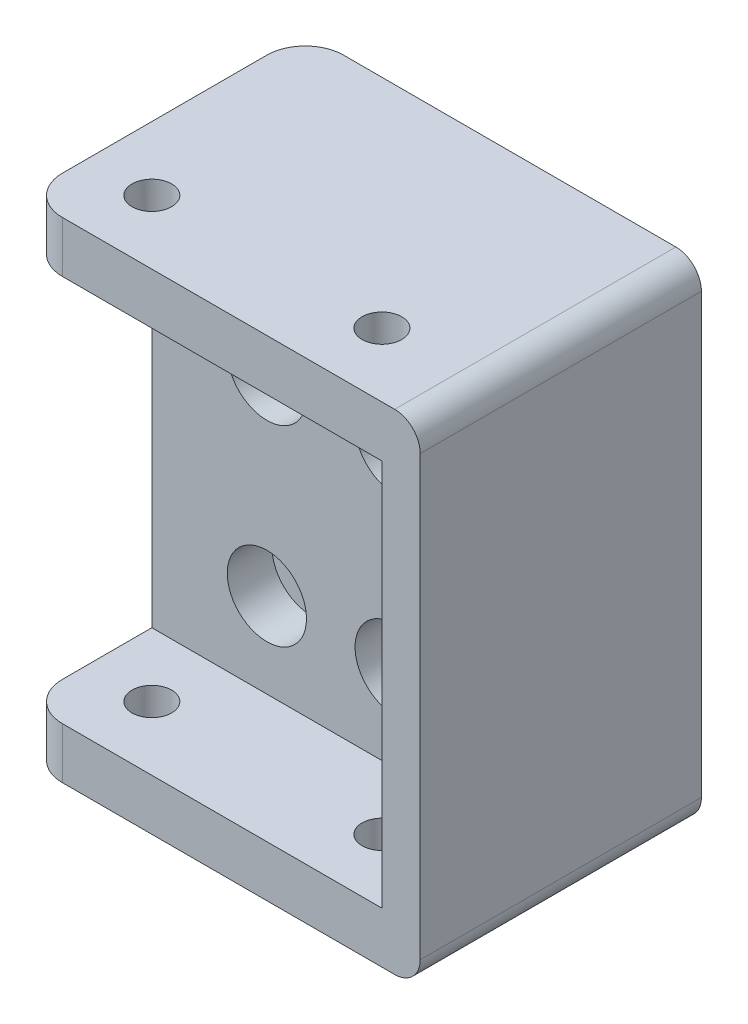
SolidWorks part; units mm, degrees
ref_plane "前视基准面" through (0, 0, 0) normal (0, 0, 1) x (1, 0, 0)
ref_plane "上视基准面" through (0, 0, 0) normal (0, 1, 0) x (1, 0, 0)
ref_plane "右视基准面" through (0, 0, 0) normal (1, 0, 0) x (0, 0, -1)
other "Configuration Table"
sketch "草图1" plane through (0, 0, 0) normal (0, 0, 1) x (1, 0, 0)
  line L1 (-5, 7.5) -> (5, 7.5) construction
  line L2 (-5, 7.5) -> (-5, -7.5) construction
  line L3 (-5, -7.5) -> (5, -7.5) construction
  line L4 (5, 7.5) -> (5, -7.5) construction
  line L5 (-5, 7.5) -> (5, -7.5) construction
  line L6 (-5, -7.5) -> (5, 7.5) construction
  line L7 (-14, 10.15) -> (14, 10.15)
  line L8 (-14, 10.15) -> (-14, -10.15)
  line L9 (-14, -10.15) -> (14, -10.15)
  line L10 (14, 10.15) -> (14, -10.15)
  line L11 (-14, 10.15) -> (14, -10.15) construction
  line L12 (-14, -10.15) -> (14, 10.15) construction
  circle A0 centre (-5, 7.5) radius 1.5
  circle A1 centre (5, 7.5) radius 1.5
  circle A2 centre (5, -7.5) radius 1.5
  circle A3 centre (-5, -7.5) radius 1.5
  point P0 (0, 0)
  point P6 (0, 0)
  dimension "D4" = 3
  dimension "D1" = 15
  dimension "D2" = 10
  dimension "D3" = 28
  dimension "D5" = 20.3
extrude "凸台-拉伸1" add sketch "草图1" along normal blind 5
sketch "草图2" plane through (0, 0, 5) normal (0, 0, 1) x (1, 0, 0)
  line L0 (-14, 0) -> (14, 0)
  line L1 (14, 10.15) -> (-14, 10.15)
  line L2 (-14, -10.15) -> (14, -10.15)
  line L3 (-14, -10.15) -> (-14, -14.15)
  line L4 (14, -10.15) -> (14, 10.15)
  line L5 (14, 10.15) -> (-14, 10.15)
  line L6 (-14, 10.15) -> (-14, -10.15)
  line L7 (-14, -10.15) -> (14, -10.15)
  line L8 (14, -10.15) -> (14, 10.15)
  line L9 (14, 10.15) -> (-14, 10.15)
  line L10 (-14, 10.15) -> (-14, -10.15)
  line L11 (-14, -10.15) -> (14, -10.15)
  line L12 (-14, -14.15) -> (14, -14.15)
  line L13 (14, -10.15) -> (14, -14.15)
  line L14 (14, 10.15) -> (14, 16.15)
  line L15 (-14, 10.15) -> (-14, 16.15)
  line L16 (14, 16.15) -> (-14, 16.15)
  line M11 (14, 10.15) -> (-14, 10.15)
  line M13 (-14, -10.15) -> (14, -10.15)
  dimension "D2" = 4
  dimension "D3" = 6
  dimension "D1" = 0
extrude "凸台-拉伸2" add sketch "草图2" against normal blind 10 contours L14 L16 L15 L1 M11 | L13 L3 L12 M13
sketch "草图3" plane through (0, 0, -5) normal (0, 0, -1) x (-1, 0, 0)
  line L4 (-14, 16.15) -> (-14, 10.15)
  line L5 (-14, 10.15) -> (14, 10.15)
  line L6 (14, 10.15) -> (14, 16.15)
  line L7 (14, 16.15) -> (-14, 16.15)
  line L8 (-14, 16.15) -> (-14, 10.15)
  line L9 (-14, 10.15) -> (14, 10.15)
  line L10 (14, 10.15) -> (14, 16.15)
  line L11 (14, 16.15) -> (-14, 16.15)
  dimension "D1" = 0
extrude "凸台-拉伸3" add sketch "草图3" along normal blind 5
sketch "草图4" plane through (0, 0, 5) normal (0, 0, 1) x (1, 0, 0)
  line L0 (14, 16.15) -> (-14, 16.15) construction
  line L2 (0, 13.15) -> (0, 0) construction
  circle A0 centre (-9, 13.15) radius 1.5
  circle A1 centre (0, 13.15) radius 1.5 construction
  circle A2 centre (9, 13.15) radius 1.5
  dimension "D1" = 3
  dimension "D2" = 3
  dimension "D5" = 9
  dimension "D4" = 3
extrude "切除-拉伸1" cut sketch "草图4" against normal through all
sketch "草图5" plane through (-14, 0, 0) normal (-1, 0, 0) x (0, 0, 1)
  line L0 (0, 16.15) -> (0, -14.15)
  line L8 (0, 10.15) -> (0, -10.15)
  line L9 (0, -10.15) -> (-5, -10.15)
  line L10 (-5, -10.15) -> (-5, -14.15)
  line L11 (-5, -14.15) -> (5, -14.15)
  line L12 (5, -14.15) -> (5, 16.15)
  line L13 (5, 16.15) -> (-10, 16.15)
  line L14 (-10, 16.15) -> (-10, 10.15)
  line L15 (-10, 10.15) -> (0, 10.15)
  line L16 (0, 10.15) -> (0, -10.15)
  line L17 (0, -10.15) -> (-5, -10.15)
  line L18 (-5, -10.15) -> (-5, -14.15)
  line L19 (-5, -14.15) -> (5, -14.15)
  line L20 (5, -14.15) -> (5, 16.15)
  line L21 (5, 16.15) -> (-10, 16.15)
  line L22 (-10, 16.15) -> (-10, 10.15)
  line L23 (-10, 10.15) -> (0, 10.15)
  line M10 (0, -10.15) -> (-5, -10.15)
  line M11 (-5, -10.15) -> (-5, -14.15)
  line M12 (-5, -14.15) -> (5, -14.15)
  line M14 (5, 16.15) -> (-10, 16.15)
  line M15 (-10, 16.15) -> (-10, 10.15)
  line M16 (-10, 10.15) -> (0, 10.15)
  dimension "D1" = 0
extrude "切除-拉伸2" cut sketch "草图5" against normal through all contours L0 M14 M15 M16 | L0 M10 M11 M12
sketch "草图6" plane through (0, 0, 5) normal (0, 0, 1) x (1, 0, 0)
  line L4 (14, -14.15) -> (14, 16.15)
  line L5 (14, 16.15) -> (-14, 16.15)
  line L6 (-14, 16.15) -> (-14, -14.15)
  line L7 (-14, -14.15) -> (14, -14.15)
  line L8 (14, -14.15) -> (14, 16.15)
  line L9 (14, 16.15) -> (-14, 16.15)
  line L10 (-14, 16.15) -> (-14, -14.15)
  line L11 (-14, -14.15) -> (14, -14.15)
  dimension "D1" = 0
extrude "切除-拉伸3" cut sketch "草图6" against normal blind 1
sketch "草图7" plane through (0, 0, 4) normal (0, 0, 1) x (1, 0, 0)
  line L0 (-14, -14.15) -> (14, -14.15)
  line L1 (-14, -14.15) -> (-14, -18.15)
  line L2 (14, -14.15) -> (14, -18.15)
  line L3 (-14, -18.15) -> (14, -18.15)
  line L4 (-14, -14.15) -> (14, -14.15)
  line L5 (14, -14.15) -> (14, 16.15)
  line L6 (14, 16.15) -> (-14, 16.15)
  line L7 (-14, 16.15) -> (-14, -14.15)
  line L8 (-14, -14.15) -> (14, -14.15)
  line L9 (14, -14.15) -> (14, 16.15)
  line L10 (14, 16.15) -> (-14, 16.15)
  line L11 (-14, 16.15) -> (-14, -14.15)
  line L12 (-14, 16.15) -> (14, 16.15)
  line L13 (-14, 16.15) -> (-14, 20.15)
  line L14 (14, 16.15) -> (14, 20.15)
  line L15 (-14, 20.15) -> (14, 20.15)
  line M11 (-14, -14.15) -> (14, -14.15)
  line M13 (14, 16.15) -> (-14, 16.15)
  dimension "D2" = 4
  dimension "D3" = 4
  dimension "D1" = 0
extrude "凸台-拉伸4" add sketch "草图7" against normal blind 10 and the other way blind 12 contours L15 L13 L14 M13 | L1 L3 L2 M11
sketch "草图9" plane through (0, 0, 4) normal (0, 0, 1) x (1, 0, 0)
  line L1 (-7.369, 10.325) -> (-5.738, 13.15)
  line L2 (-5.738, 13.15) -> (-7.369, 15.975)
  line L3 (-7.369, 15.975) -> (-10.631, 15.975)
  line L4 (-10.631, 15.975) -> (-12.262, 13.15)
  line L5 (-12.262, 13.15) -> (-10.631, 10.325)
  line L6 (-10.631, 10.325) -> (-7.369, 10.325)
  line L7 (10.631, 10.325) -> (12.262, 13.15)
  line L8 (12.262, 13.15) -> (10.631, 15.975)
  line L9 (10.631, 15.975) -> (7.369, 15.975)
  line L10 (7.369, 15.975) -> (5.738, 13.15)
  line L11 (5.738, 13.15) -> (7.369, 10.325)
  line L12 (7.369, 10.325) -> (10.631, 10.325)
  circle A0 centre (5, -7.5) radius 1.5 construction
  circle A1 centre (-5, -7.5) radius 1.5 construction
  circle A2 centre (9, 13.15) radius 1.5 construction
  circle A3 centre (5, 7.5) radius 1.5 construction
  circle A4 centre (-5, 7.5) radius 1.5 construction
  circle A5 centre (-9, 13.15) radius 1.5 construction
  circle A6 centre (5, -7.5) radius 1.5
  circle A7 centre (-5, -7.5) radius 1.5
  circle A8 centre (9, 13.15) radius 1.5
  circle A9 centre (5, 7.5) radius 1.5
  circle A10 centre (-5, 7.5) radius 1.5
  circle A11 centre (-9, 13.15) radius 1.5
  circle A13 centre (-5, 7.5) radius 3.1
  circle A14 centre (5, 7.5) radius 3.1
  circle A16 centre (5, -7.5) radius 3.1
  circle A17 centre (-5, -7.5) radius 3.1
  circle A18 centre (-9, 13.15) radius 2.825 construction
  circle A19 centre (9, 13.15) radius 2.825 construction
  dimension "D1" = 5.65
  dimension "D2" = 1.6
extrude "切除-拉伸4" cut sketch "草图9" against normal blind 1.5 and the other way through all
sketch "草图10" plane through (0, -14.15, 0) normal (0, 1, 0) x (1, 0, 0)
  line L0 (0, -4) -> (0, -16)
  line L4 (14, -4) -> (-14, -4)
  line L5 (-14, -4) -> (-14, -16)
  line L6 (-14, -16) -> (14, -16)
  line L7 (14, -16) -> (14, -4)
  line L8 (14, -4) -> (-14, -4)
  line L9 (-14, -4) -> (-14, -16)
  line L10 (-14, -16) -> (14, -16)
  line L11 (14, -16) -> (14, -4)
  circle A0 centre (-9, -11) radius 1.55
  circle A1 centre (9, -11) radius 1.55
  dimension "D2" = 3.1
  dimension "D3" = 5
  dimension "D4" = 5
  dimension "D1" = 0
extrude "切除-拉伸5" cut sketch "草图10" against normal through all and the other way through all contours A0 | A1
sketch "草图11" plane through (14, 0, 0) normal (1, 0, 0) x (0, 0, -1)
  line L0 (-16, 16.15) -> (-16, -14.15)
  line L1 (6, 18.4397) -> (6, -14.15)
  line L12 (-4, 16.15) -> (-4, -14.15)
  line L13 (-4, -14.15) -> (-16, -14.15)
  line L14 (-16, -14.15) -> (-16, -18.15)
  line L15 (-16, -18.15) -> (6, -18.15)
  line L16 (6, -18.15) -> (6, -14.15)
  line L17 (6, -14.15) -> (0, -14.15)
  line L18 (0, -14.15) -> (0, 16.15)
  line L19 (0, 16.15) -> (6, 16.15)
  line L20 (6, 16.15) -> (6, 20.15)
  line L21 (6, 20.15) -> (-16, 20.15)
  line L22 (-16, 20.15) -> (-16, 16.15)
  line L23 (-16, 16.15) -> (-4, 16.15)
  line L24 (-4, 16.15) -> (-4, -14.15)
  line L25 (-4, -14.15) -> (-16, -14.15)
  line L26 (-16, -14.15) -> (-16, -18.15)
  line L27 (-16, -18.15) -> (6, -18.15)
  line L28 (6, -18.15) -> (6, -14.15)
  line L29 (6, -14.15) -> (0, -14.15)
  line L30 (0, -14.15) -> (0, 16.15)
  line L31 (0, 16.15) -> (6, 16.15)
  line L32 (6, 16.15) -> (6, 20.15)
  line L33 (6, 20.15) -> (-16, 20.15)
  line L34 (-16, 20.15) -> (-16, 16.15)
  line L38 (-16, 16.15) -> (-4, 16.15)
  line M13 (-4, 16.15) -> (-4, -14.15)
  line M14 (-4, -14.15) -> (-16, -14.15)
  line M15 (-16, -14.15) -> (-16, -18.15)
  line M16 (-16, -18.15) -> (6, -18.15)
  line M17 (6, -18.15) -> (6, -14.15)
  line M18 (6, -14.15) -> (0, -14.15)
  line M19 (0, -14.15) -> (0, 16.15)
  line M20 (0, 16.15) -> (6, 16.15)
  line M21 (6, 16.15) -> (6, 20.15)
  line M22 (6, 20.15) -> (-16, 20.15)
  line M23 (-16, 20.15) -> (-16, 16.15)
  line M24 (-16, 16.15) -> (-4, 16.15)
  dimension "D1" = 0
extrude "凸台-拉伸5" add sketch "草图11" along normal blind 3 contours M24 M13 M14 M15 M16 M17 M18 M19 M20 M21 M22 M23 | L0 M24 M14 M13 | L1 M20 M19 M18
fillet "圆角1" radius 2 2 edges at (17, -18.15, 5) (17, 20.15, 5)
fillet "圆角2" radius 3 4 edges at (-14, 18.15, 16) (-14, 18.15, -6) (-14, -16.15, -6) (-14, -16.15, 16)
sketch "草图13" plane through (0, 0, 4) normal (0, 0, 1) x (1, 0, 0)
  line L0 (-10.631, 15.975) -> (-7.369, 15.975) construction
  line L1 (-12.262, 13.15) -> (-10.631, 15.975) construction
  line L2 (-10.631, 15.975) -> (-7.369, 15.975)
  line L3 (-12.262, 13.15) -> (-10.631, 15.975)
  line L4 (-7.369, 15.975) -> (-5.738, 13.15) construction
  line L5 (-5.738, 13.15) -> (-7.369, 10.325) construction
  line L6 (14, 16.15) -> (-14, 16.15)
  line L7 (-7.369, 10.325) -> (-10.631, 10.325) construction
  line L8 (-10.631, 10.325) -> (-12.262, 13.15) construction
  line L9 (-14, 16.15) -> (-14, -14.15)
  line L10 (-14, -14.15) -> (14, -14.15)
  line L11 (14, -14.15) -> (14, 16.15)
  line L12 (14, 16.15) -> (-14, 16.15)
  line L15 (-14, 16.15) -> (-14, -14.15)
  line L16 (-14, -14.15) -> (14, -14.15)
  line L17 (14, -14.15) -> (14, 16.15)
  line L18 (-7.369, 15.975) -> (-5.738, 13.15)
  line L19 (-5.738, 13.15) -> (-7.369, 10.325)
  line L20 (-7.369, 10.325) -> (-10.631, 10.325)
  line L21 (-10.631, 10.325) -> (-12.262, 13.15)
  line L22 (10.631, 10.325) -> (7.369, 10.325) construction
  line L23 (7.369, 10.325) -> (5.738, 13.15) construction
  line L24 (12.262, 13.15) -> (10.631, 10.325) construction
  line L25 (10.631, 15.975) -> (12.262, 13.15) construction
  line L26 (7.369, 15.975) -> (10.631, 15.975) construction
  line L27 (5.738, 13.15) -> (7.369, 15.975) construction
  line L28 (10.631, 10.325) -> (7.369, 10.325)
  line L29 (7.369, 10.325) -> (5.738, 13.15)
  line L30 (12.262, 13.15) -> (10.631, 10.325)
  line L31 (10.631, 15.975) -> (12.262, 13.15)
  line L32 (7.369, 15.975) -> (10.631, 15.975)
  line L33 (5.738, 13.15) -> (7.369, 15.975)
  circle A1 centre (5, -7.5) radius 3.1
  circle A6 centre (5, -7.5) radius 3.1
  circle A7 centre (-5, -7.5) radius 3.1
  circle A8 centre (-5, -7.5) radius 3.1
  circle A9 centre (5, 7.5) radius 3.1
  circle A10 centre (5, 7.5) radius 3.1
  circle A11 centre (-5, 7.5) radius 3.1
  circle A12 centre (-5, 7.5) radius 3.1
  dimension "D1" = 0
  dimension "D2" = 0
  dimension "D3" = 0
  dimension "D4" = 0
  dimension "D5" = 0
extrude "凸台-拉伸6" add sketch "草图13" along normal blind 2
